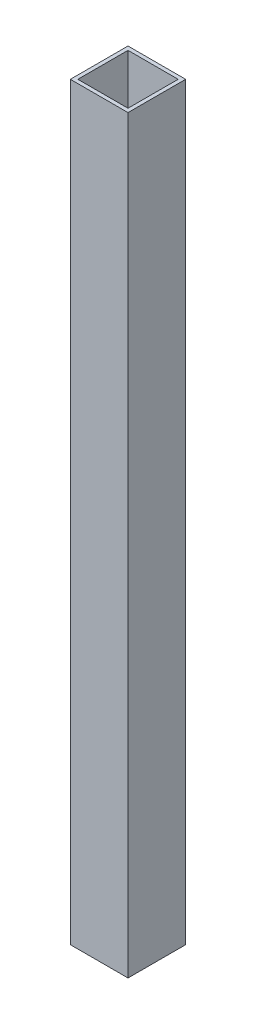
SolidWorks part; units mm, degrees
material "6061 Alloy"
ref_plane "Front Plane" through (0, 0, 0) normal (0, 0, 1) x (1, 0, 0)
ref_plane "Top Plane" through (0, 0, 0) normal (0, 1, 0) x (1, 0, 0)
ref_plane "Right Plane" through (0, 0, 0) normal (1, 0, 0) x (0, 0, -1)
sketch "Sketch1" plane through (0, 0, 0) normal (0, 1, 0) x (1, 0, 0)
  line L1 (-12.7, -12.7) -> (12.7, -12.7)
  line L2 (-12.7, -12.7) -> (-12.7, 12.7)
  line L3 (-12.7, 12.7) -> (12.7, 12.7)
  line L4 (12.7, -12.7) -> (12.7, 12.7)
  line L5 (-12.7, -12.7) -> (12.7, 12.7) construction
  line L6 (-12.7, 12.7) -> (12.7, -12.7) construction
  point P0 (0, 0)
  dimension "D1" = 25.4
  dimension "D2" = 25.4
extrude "Boss-Extrude1" add sketch "Sketch1" along normal mid plane 330.2 contours L2 L1 L4 L3
sketch "Sketch2" plane through (0, 165.1, 0) normal (0, 1, 0) x (1, 0, 0)
  line L0 (-12.7, -12.7) -> (-12.7, 12.7) construction
  line L1 (-11.049, -11.049) -> (11.049, -11.049)
  line L2 (-11.049, -11.049) -> (-11.049, 11.049)
  line L3 (-11.049, 11.049) -> (11.049, 11.049)
  line L4 (11.049, -11.049) -> (11.049, 11.049)
  line L5 (-11.049, -11.049) -> (11.049, 11.049) construction
  line L6 (-11.049, 11.049) -> (11.049, -11.049) construction
  line L7 (-12.7, 12.7) -> (12.7, 12.7) construction
  point P0 (0, 0)
  dimension "D1" = 1.651
  dimension "D2" = 1.651
extrude "Cut-Extrude1" cut sketch "Sketch2" against normal through all contours L2 L1 L4 L3
